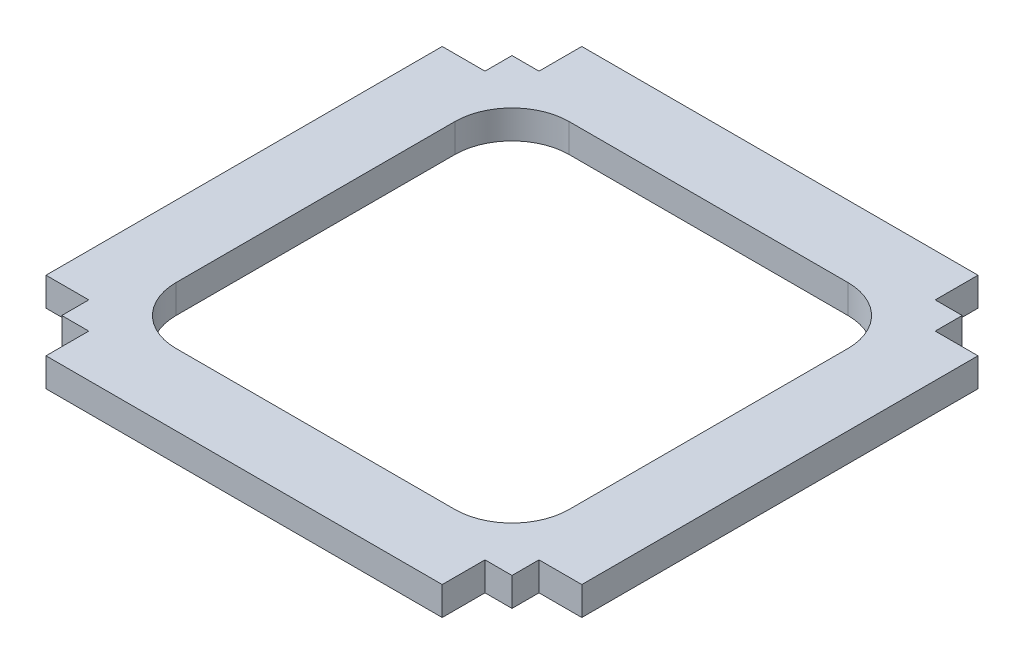
SolidWorks part; units mm, degrees
ref_plane "Front" through (0, 0, 0) normal (0, 0, 1) x (1, 0, 0)
ref_plane "Top" through (0, 0, 0) normal (0, 1, 0) x (1, 0, 0)
ref_plane "Right" through (0, 0, 0) normal (1, 0, 0) x (0, 0, -1)
sketch "Sketch1" plane through (0, 0, 0) normal (0, 1, 0) x (1, 0, 0)
  line L0 (-44, 50) -> (-50, 50)
  line L1 (50, -50) -> (44, -50)
  line L2 (50, -50) -> (50, -44)
  line L3 (50, 50) -> (44, 50)
  line L4 (-50, -50) -> (-50, -44)
  line L7 (44, -59.5) -> (-44, -59.5)
  line L8 (44, -59.5) -> (44, -50)
  line L9 (44, 59.5) -> (-44, 59.5)
  line L10 (-44, -59.5) -> (-44, -50)
  line L13 (59.5, -44) -> (50, -44)
  line L14 (59.5, -44) -> (59.5, 44)
  line L15 (59.5, 44) -> (50, 44)
  line L16 (-59.5, -44) -> (-59.5, 44)
  line L19 (-50, 44) -> (-59.5, 44)
  line L20 (-50, -44) -> (-59.5, -44)
  line L21 (-44, -50) -> (-50, -50)
  line L22 (50, 44) -> (50, 50)
  line L23 (44, 50) -> (44, 59.5)
  line L25 (-44, 50) -> (-44, 59.5)
  line L26 (-50, 44) -> (-50, 50)
  point P0 (0, 0)
  point P6 (0, 0)
  point P11 (0, 0)
  dimension "D1" = 100
  dimension "D2" = 100
  dimension "D3" = 119
  dimension "D4" = 119
  dimension "D5" = 88
  dimension "D6" = 88
extrude "Boss-Extrude1" add sketch "Sketch1" along normal blind 6.35
sketch "Sketch2" plane through (0, 6.35, 0) normal (0, 1, 0) x (1, 0, 0)
  line L0 (-44, 50) -> (-50, 50) construction
  line L1 (43.65, -43.65) -> (-43.65, -43.65)
  line L2 (43.65, -43.65) -> (43.65, 43.65)
  line L3 (43.65, 43.65) -> (-43.65, 43.65)
  line L4 (-43.65, -43.65) -> (-43.65, 43.65)
  line L5 (43.65, -43.65) -> (-43.65, 43.65) construction
  line L6 (43.65, 43.65) -> (-43.65, -43.65) construction
  line L7 (-50, 50) -> (-50, 44) construction
  point P0 (0, 0)
  point P8 (-47, 50)
  point P11 (-50, 47)
  dimension "D1" = 6.35
  dimension "D2" = 6.35
extrude "Cut-Extrude1" cut sketch "Sketch2" against normal blind 6.35
fillet "Fillet1" radius 12.7 4 edges at (-43.65, 3.175, 43.65) (43.65, 3.175, 43.65) (43.65, 3.175, -43.65) (-43.65, 3.175, -43.65)
sketch "Sketch3" plane through (0, 6.35, 0) normal (0, 1, 0) x (1, 0, 0)
  line L0 (-44, 59.5) -> (-44, 50)
  line L1 (-44, 50) -> (-50, 50)
  line L2 (-50, 50) -> (-50, 44)
  line L3 (-50, 44) -> (-59.5, 44)
  line L4 (-59.5, 44) -> (-59.5, -44)
  line L5 (-59.5, -44) -> (-50, -44)
  line L6 (-50, -44) -> (-50, -50)
  line L7 (-50, -50) -> (-44, -50)
  line L8 (-44, -50) -> (-44, -59.5)
  line L9 (-44, -59.5) -> (44, -59.5)
  line L10 (44, -59.5) -> (44, -50)
  line L11 (44, -50) -> (50, -50)
  line L12 (50, -50) -> (50, -44)
  line L13 (50, -44) -> (59.5, -44)
  line L14 (59.5, -44) -> (59.5, 44)
  line L15 (59.5, 44) -> (50, 44)
  line L16 (50, 44) -> (50, 50)
  line L17 (50, 50) -> (44, 50)
  line L18 (44, 50) -> (44, 59.5)
  line L19 (44, 59.5) -> (-44, 59.5)
  line L20 (-30.95, 43.65) -> (30.95, 43.65)
  line L21 (43.65, 30.95) -> (43.65, -30.95)
  line L22 (30.95, -43.65) -> (-30.95, -43.65)
  line L23 (-43.65, -30.95) -> (-43.65, 30.95)
  arc A0 (-30.95, 43.65) -> (-43.65, 30.95) centre (-30.95, 30.95) ccw
  arc A1 (30.95, 43.65) -> (43.65, 30.95) centre (30.95, 30.95) cw
  arc A2 (-43.65, -30.95) -> (-30.95, -43.65) centre (-30.95, -30.95) ccw
  arc A3 (43.65, -30.95) -> (30.95, -43.65) centre (30.95, -30.95) cw
